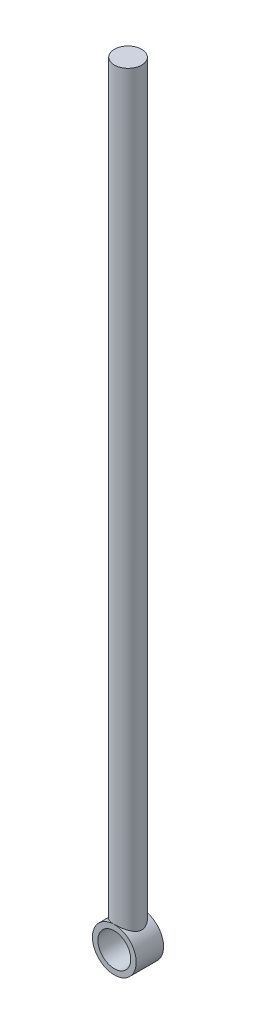
SolidWorks part; units mm, degrees
ref_plane "前视基准面" through (0, 0, 0) normal (0, 0, 1) x (1, 0, 0)
ref_plane "上视基准面" through (0, 0, 0) normal (0, 1, 0) x (1, 0, 0)
ref_plane "右视基准面" through (0, 0, 0) normal (1, 0, 0) x (0, 0, -1)
other "Configuration Table"
sketch "草图1" plane through (0, 0, 0) normal (0, 0, 1) x (1, 0, 0)
  circle A0 centre (0, 0) radius 4
  dimension "D1" = 8
extrude "凸台-拉伸1" add sketch "草图1" along normal blind 5
sketch "草图3" plane through (0, 0, 0) normal (0, 1, 0) x (1, 0, 0)
  circle A0 centre (0, -2.491) radius 2.5
  dimension "D1" = 5
extrude "凸台-拉伸2" add sketch "草图3" along normal blind 140
sketch "草图2" plane through (0, 0, 5) normal (0, 0, 1) x (1, 0, 0)
  circle A0 centre (0, 0) radius 3
  dimension "D1" = 6
extrude "切除-拉伸1" cut sketch "草图2" against normal blind 5
